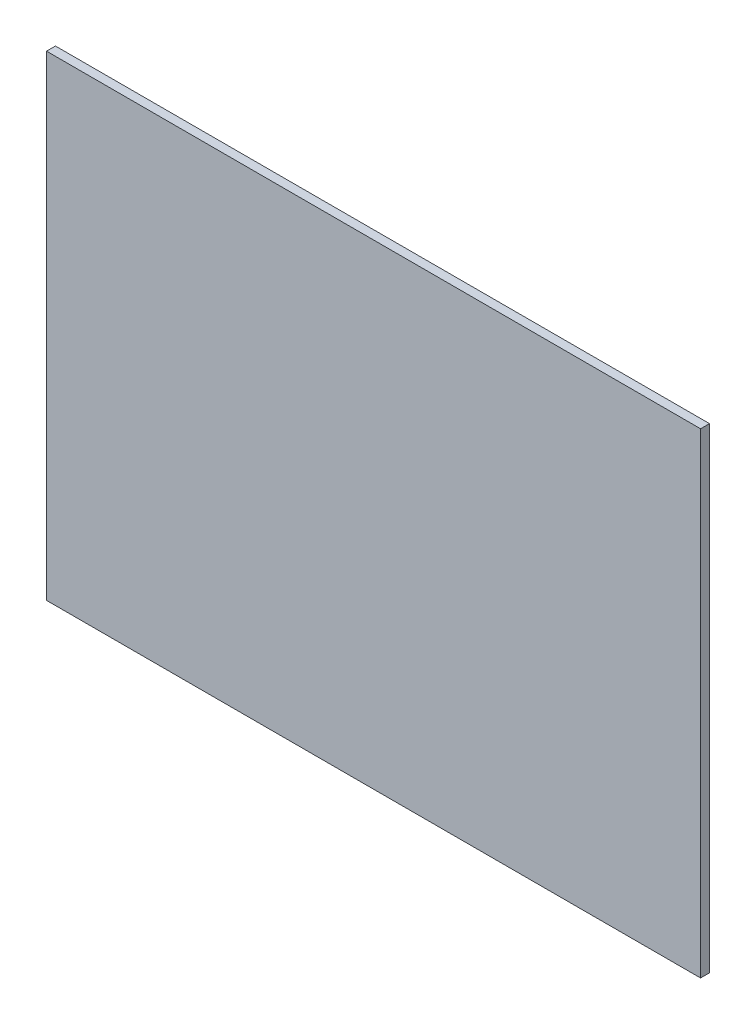
SolidWorks part; units mm, degrees
ref_plane "Piano frontale" through (0, 0, 0) normal (0, 0, 1) x (1, 0, 0)
ref_plane "Piano superiore" through (0, 0, 0) normal (0, 1, 0) x (1, 0, 0)
ref_plane "Piano destro" through (0, 0, 0) normal (1, 0, 0) x (0, 0, -1)
sketch "Schizzo1" plane through (0, 0, 0) normal (0, 0, 1) x (1, 0, 0)
  line L1 (0, 0) -> (-110, 0)
  line L2 (0, 0) -> (0, 80)
  line L3 (0, 80) -> (-110, 80)
  line L4 (-110, 0) -> (-110, 80)
  dimension "D1" = 80
  dimension "D2" = 110
extrude "Estrusione-Estrusione1" add sketch "Schizzo1" along normal blind 1.5
